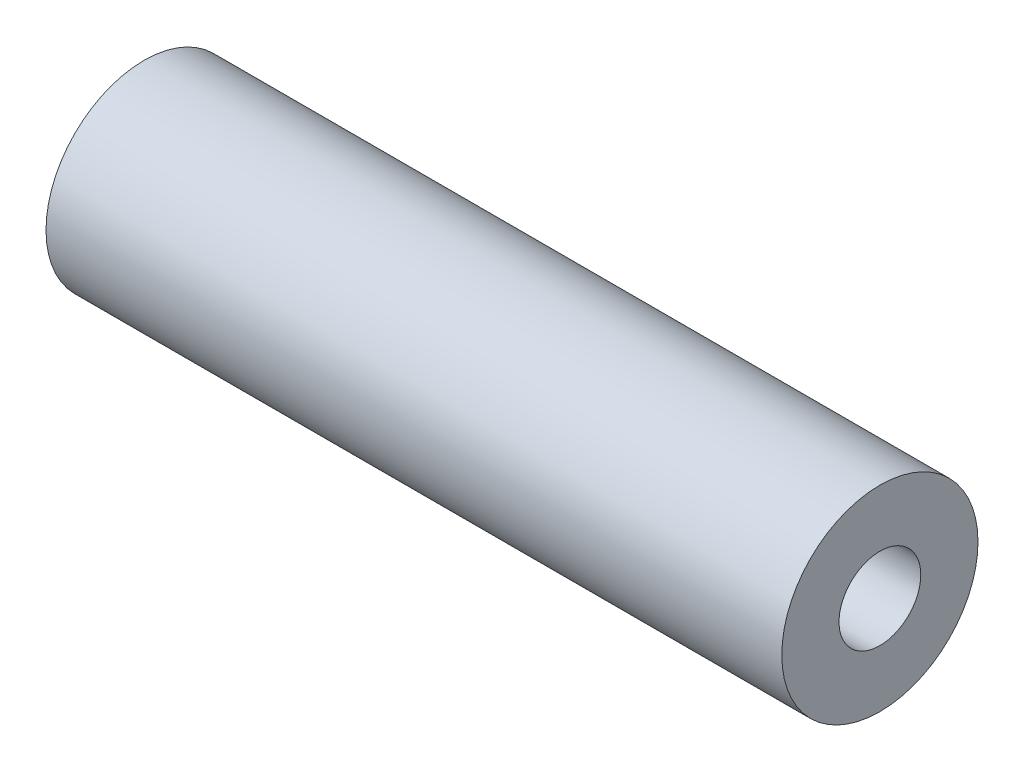
SolidWorks part; units mm, degrees
ref_plane "Front" through (0, 0, 0) normal (0, 0, 1) x (1, 0, 0)
ref_plane "Top" through (0, 0, 0) normal (0, 1, 0) x (1, 0, 0)
ref_plane "Right" through (0, 0, 0) normal (1, 0, 0) x (0, 0, -1)
sketch "Sketch1" plane through (0, 0, 0) normal (1, 0, 0) x (0, 0, -1)
  circle A0 centre (0, 0) radius 7.2
  circle A1 centre (0, 0) radius 3
  dimension "D1" = 14.4
  dimension "D2" = 6
extrude "Boss-Extrude1" add sketch "Sketch1" along normal blind 54
scale "Scale1" scale about centroid uniform scaling yes scale factor 1.05
